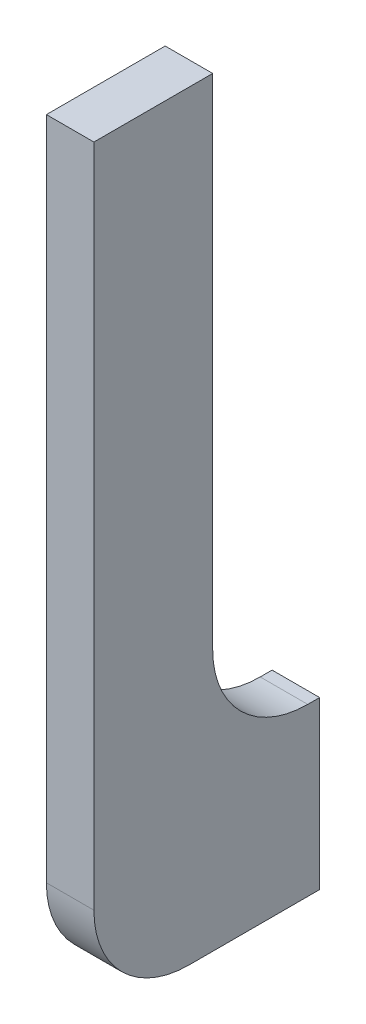
SolidWorks part; units mm, degrees
ref_plane "Front Plane" through (0, 0, 0) normal (0, 0, 1) x (1, 0, 0)
ref_plane "Top Plane" through (0, 0, 0) normal (0, 1, 0) x (1, 0, 0)
ref_plane "Right Plane" through (0, 0, 0) normal (1, 0, 0) x (0, 0, -1)
sketch "Sketch1" plane through (0, 0, 0) normal (0, 0, 1) x (1, 0, 0)
  line L0 (0, 0) -> (0, 15)
  line L1 (0, 15) -> (2, 15)
  line L2 (2, 15) -> (2, 4.9716)
  line L6 (0, 0) -> (0, -17)
  line L13 (0, -17) -> (2, -17)
  line L14 (2, -17) -> (2, 4.9716)
  dimension "D1" = 2
  dimension "D2" = 15
  dimension "D3" = 17
extrude "Boss-Extrude1" add sketch "Sketch1" along normal blind 5
sketch "Sketch2" plane through (0, 0, 0) normal (0, 0, -1) x (-1, 0, 0)
  line L0 (0, -9.998) -> (-2, -9.998)
  line L4 (-2, -17) -> (0, -17)
  line L5 (0, -17) -> (0, 15)
  line L6 (0, 15) -> (-2, 15)
  line L7 (-2, 15) -> (-2, -17)
  line L8 (-2, -17) -> (0, -17)
  line L9 (0, -17) -> (0, -9.998)
  line L11 (-2, -9.998) -> (-2, -17)
  dimension "D1" = 0
extrude "Boss-Extrude2" add sketch "Sketch2" along normal blind 4.5
fillet "Fillet1" radius 4 2 edges at (1, -17, 5) (1, -9.998, 0)
